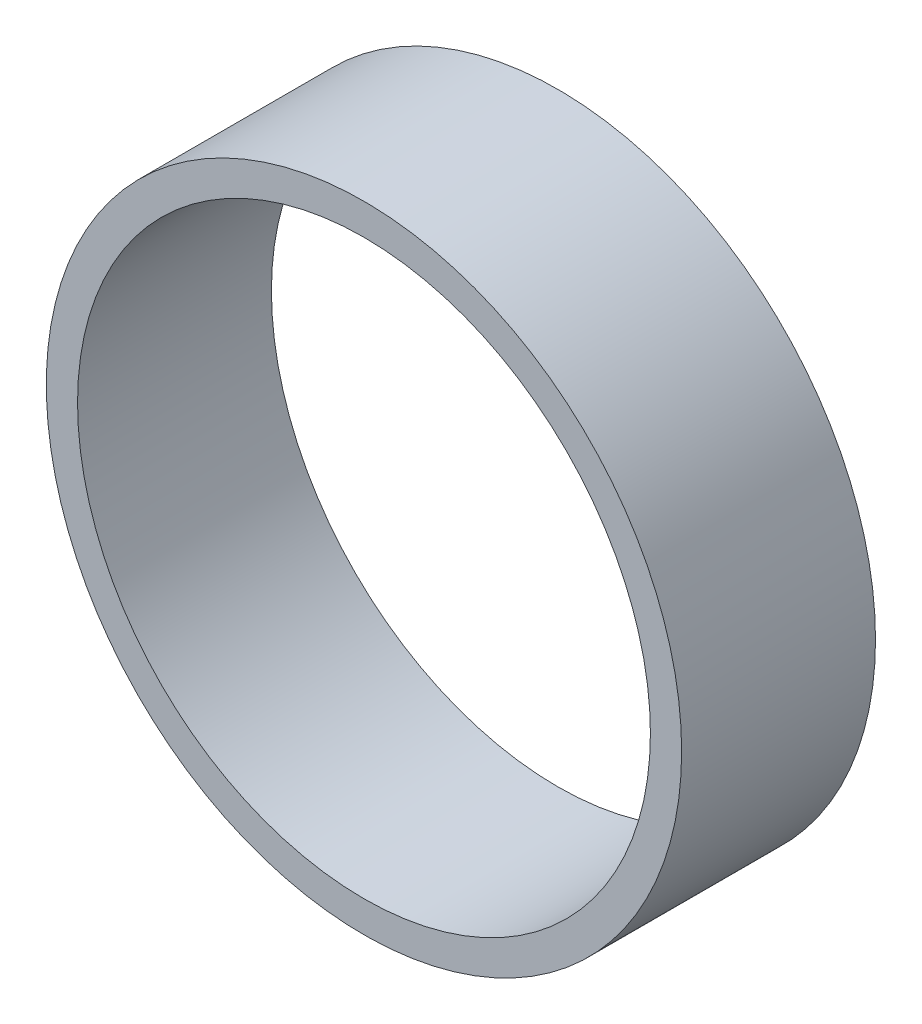
SolidWorks part; units mm, degrees
material "6061-T6 (SS)"
ref_plane "Front Plane" through (0, 0, 0) normal (0, 0, 1) x (1, 0, 0)
ref_plane "Top Plane" through (0, 0, 0) normal (0, 1, 0) x (1, 0, 0)
ref_plane "Right Plane" through (0, 0, 0) normal (1, 0, 0) x (0, 0, -1)
sketch "Sketch1" plane through (0, 0, 0) normal (1, 0, 0) x (0, 0, -1)
  line L0 (-35.627, 0) -> (36.4528, 0) construction
  line L1 (-8.4772, 25.05) -> (8.4772, 25.05)
  line L2 (-8.4772, 25.05) -> (-8.4772, 27.7812)
  line L3 (8.4772, 25.05) -> (8.4772, 27.7812)
  line L4 (-8.4772, 27.7812) -> (8.4772, 27.7812)
  line L5 (0, 0) -> (0, 25.05) construction
  dimension "D1" = 50.1
  dimension "D2" = 55.5625
  dimension "D3" = 16.9545
revolve "Revolve1" add sketch "Sketch1" angle 360 about L0
